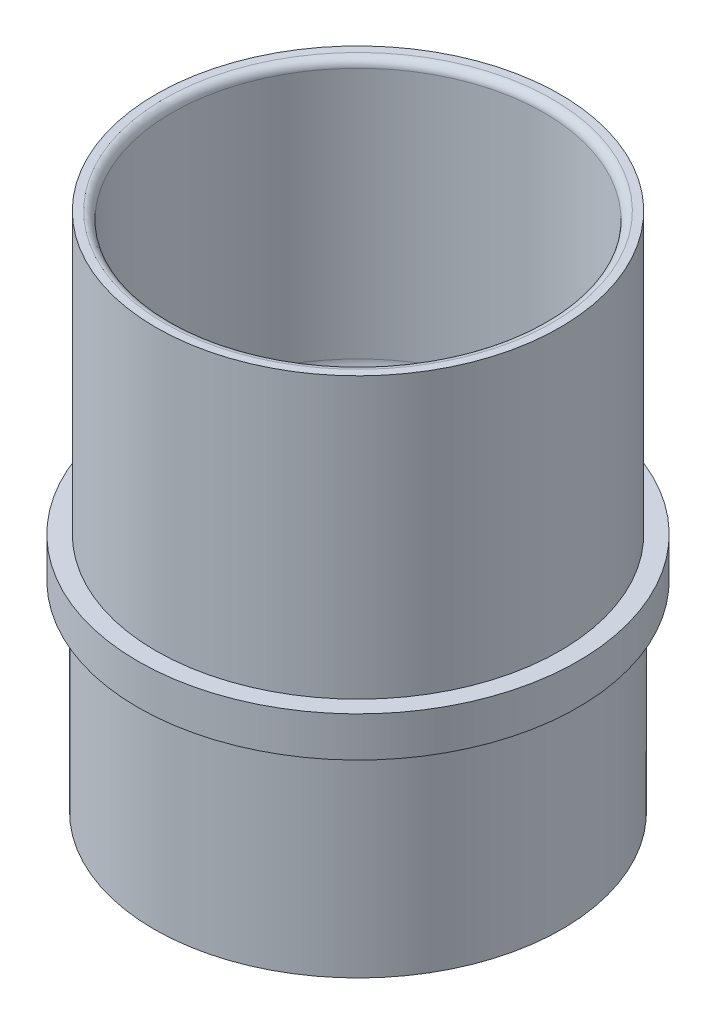
SolidWorks part; units mm, degrees
ref_plane "Front Plane" through (0, 0, 0) normal (0, 0, 1) x (1, 0, 0)
ref_plane "Top Plane" through (0, 0, 0) normal (0, 1, 0) x (1, 0, 0)
ref_plane "Right Plane" through (0, 0, 0) normal (1, 0, 0) x (0, 0, -1)
sketch "Sketch1" plane through (0, 0, 0) normal (0, 1, 0) x (1, 0, 0)
  circle A0 centre (0, 0) radius 25.5
  circle A1 centre (0, 0) radius 23.5
  dimension "D1" = 51
  dimension "D2" = 47
extrude "Boss-Extrude1" add sketch "Sketch1" along normal blind 25
sketch "Sketch2" plane through (0, 25, 0) normal (0, 1, 0) x (1, 0, 0)
  circle A0 centre (0, 0) radius 27.5
  dimension "D1" = 55
extrude "Boss-Extrude2" add sketch "Sketch2" along normal blind 5
sketch "Sketch3" plane through (0, 30, 0) normal (0, 1, 0) x (1, 0, 0)
  circle A0 centre (0, 0) radius 23.25
  circle A1 centre (0, 0) radius 25.25
  dimension "D1" = 50.5
  dimension "D2" = 46.5
extrude "Boss-Extrude3" add sketch "Sketch3" along normal blind 35
fillet "Fillet1" radius 2.54 1 edges at (0, 30, 23.25)
fillet "Fillet2" radius 1 1 edges at (0, 65, 23.25)
